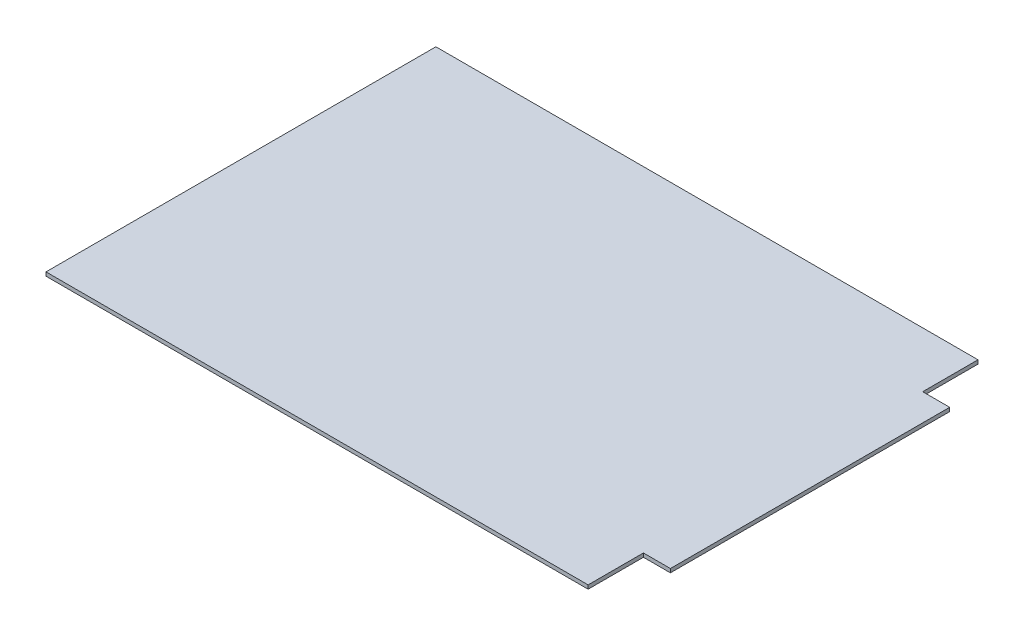
SolidWorks part; units mm, degrees
ref_plane "Alzado" through (0, 0, 0) normal (0, 0, 1) x (1, 0, 0)
ref_plane "Planta" through (0, 0, 0) normal (0, 1, 0) x (1, 0, 0)
ref_plane "Vista lateral" through (0, 0, 0) normal (1, 0, 0) x (0, 0, -1)
sketch "Croquis2" plane through (0, 0, 0) normal (0, 1, 0) x (1, 0, 0)
  line L1 (-210.93, 144.5) -> (210.93, 144.5)
  line L2 (-210.93, 144.5) -> (-210.93, -144.5)
  line L3 (-210.93, -144.5) -> (210.93, -144.5)
  line L4 (210.93, 144.5) -> (210.93, -144.5)
  line L5 (-210.93, 144.5) -> (210.93, -144.5) construction
  line L6 (-210.93, -144.5) -> (210.93, 144.5) construction
  point P0 (0, 0)
  dimension "D1" = 421.86
  dimension "D2" = 289
extrude "Saliente-Extruir1" add sketch "Croquis2" along normal blind 2.8
sketch "Croquis3" plane through (0, 2.8, 0) normal (0, 1, 0) x (1, 0, 0)
  line L0 (210.93, 144.5) -> (-210.93, 144.5) construction
  line L1 (210.93, -144.5) -> (190.93, -144.5)
  line L2 (210.93, -144.5) -> (210.93, -103.5)
  line L3 (210.93, -103.5) -> (190.93, -103.5)
  line L4 (190.93, -144.5) -> (190.93, -103.5)
  line L5 (210.93, 144.5) -> (190.93, 144.5)
  line L6 (210.93, 144.5) -> (210.93, 103.5)
  line L7 (210.93, 103.5) -> (190.93, 103.5)
  line L8 (190.93, 144.5) -> (190.93, 103.5)
  line L9 (210.93, -144.5) -> (210.93, 144.5) construction
  dimension "D1" = 41
  dimension "D2" = 20
  dimension "D3" = 41
  dimension "D4" = 20
extrude "Cortar-Extruir1" cut sketch "Croquis3" against normal blind 2.8 contours L6 L5 L8 L7 | L2 L1 L4 L3
